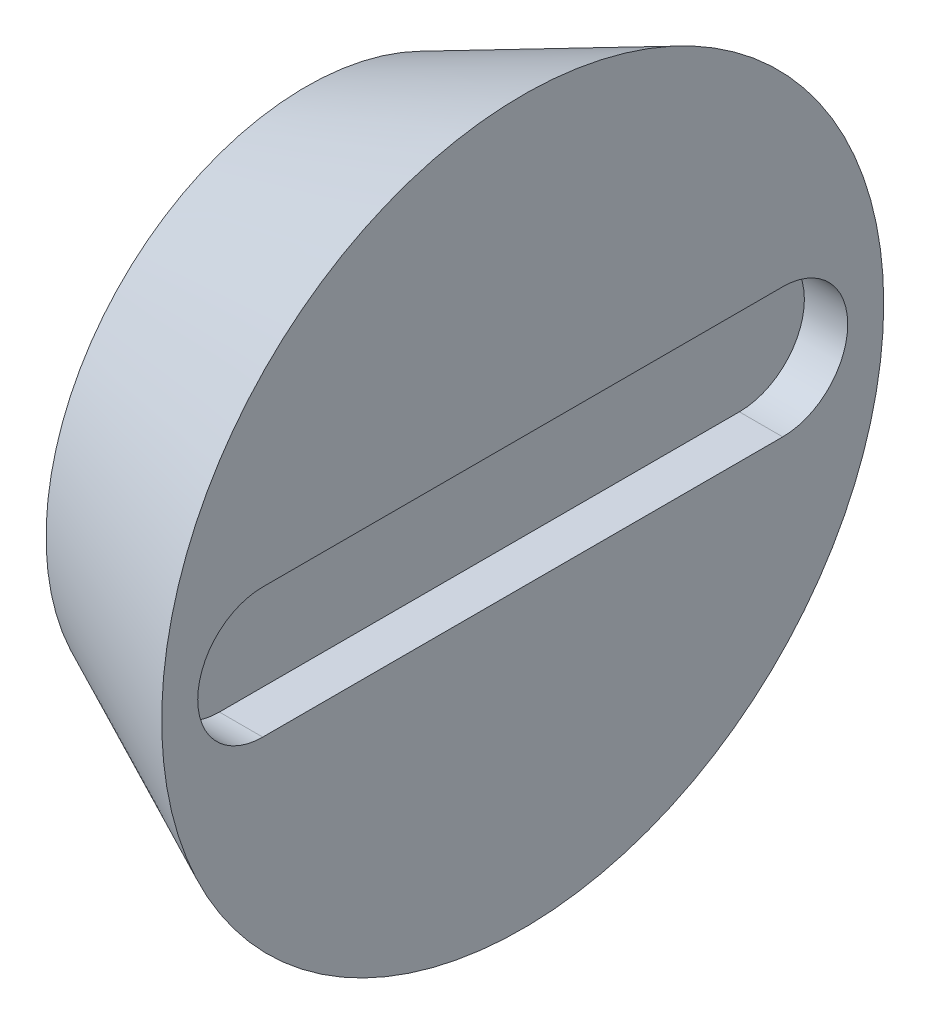
SolidWorks part; units mm, degrees
material "PE High Density"
ref_plane "Front Plane" through (0, 0, 0) normal (0, 0, 1) x (1, 0, 0)
ref_plane "Top Plane" through (0, 0, 0) normal (0, 1, 0) x (1, 0, 0)
ref_plane "Right Plane" through (0, 0, 0) normal (1, 0, 0) x (0, 0, -1)
sketch "Sketch1" plane through (0, 0, 0) normal (1, 0, 0) x (0, 0, -1)
  circle A0 centre (0, 0) radius 30
  dimension "D1" = 60
extrude "Boss-Extrude1" add sketch "Sketch1" along normal blind 25 draft 25 draft outward yes
sketch "Sketch2" plane through (25, 0, 0) normal (1, 0, 0) x (0, 0, -1)
  line L0 (-30, 0) -> (30, 0) construction
  line L1 (-30, 7.5) -> (30, 7.5)
  line L2 (-30, -7.5) -> (30, -7.5)
  arc A0 (-30, 7.5) -> (-30, -7.5) centre (-30, 0) ccw
  arc A1 (30, -7.5) -> (30, 7.5) centre (30, 0) ccw
  point P4 (0, 0)
  dimension "D1" = 15
  dimension "D2" = 60
extrude "Cut-Extrude1" cut sketch "Sketch2" against normal blind 5
